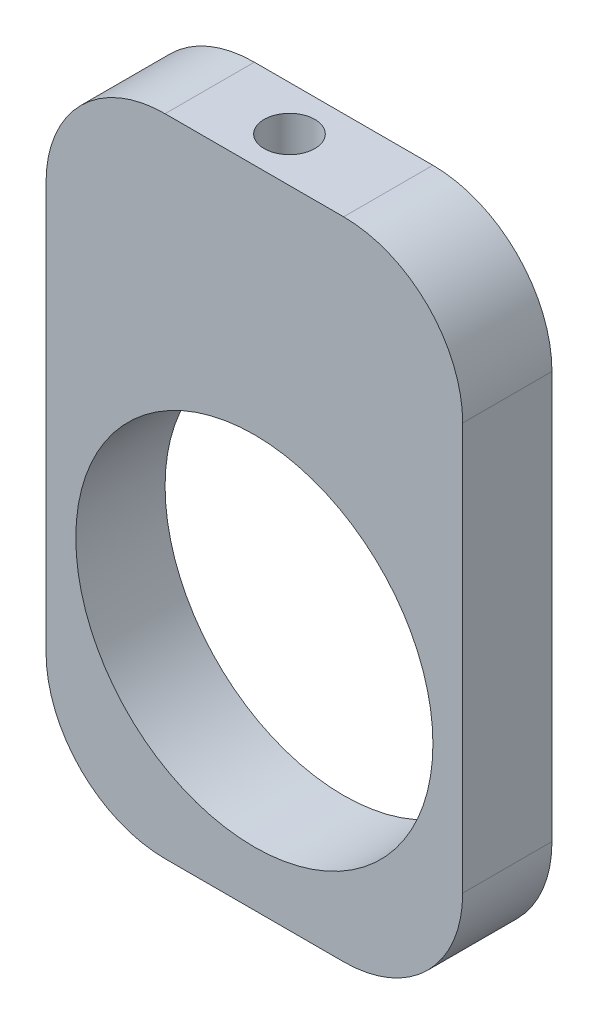
SolidWorks part; units mm, degrees
material "6063-O"
ref_plane "Front" through (0, 0, 0) normal (0, 0, 1) x (1, 0, 0)
ref_plane "Top" through (0, 0, 0) normal (0, 1, 0) x (1, 0, 0)
ref_plane "Right" through (0, 0, 0) normal (1, 0, 0) x (0, 0, -1)
sketch "Sketch1" plane through (0, 0, 0) normal (0, 0, 1) x (1, 0, 0)
  line L0 (11.1125, 12.446) -> (11.1125, 15.621)
  line L1 (4.7625, -12.446) -> (-4.7625, -12.446)
  line L2 (11.1125, -6.096) -> (11.1125, 12.446)
  line L3 (11.1125, 12.446) -> (-11.1125, 12.446)
  line L4 (-11.1125, -6.096) -> (-11.1125, 12.446)
  line L5 (11.1125, -12.446) -> (-11.1125, 12.446) construction
  line L6 (11.1125, 12.446) -> (-11.1125, -12.446) construction
  line L7 (4.7625, 21.971) -> (-4.7625, 21.971)
  line L8 (-11.1125, 15.621) -> (-11.1125, 12.446)
  circle A0 centre (0, 0) radius 9.525
  arc A1 (-11.1125, -6.096) -> (-4.7625, -12.446) centre (-4.7625, -6.096) ccw
  arc A2 (4.7625, -12.446) -> (11.1125, -6.096) centre (4.7625, -6.096) ccw
  arc A3 (11.1125, 15.621) -> (4.7625, 21.971) centre (4.7625, 15.621) ccw
  arc A4 (-4.7625, 21.971) -> (-11.1125, 15.621) centre (-4.7625, 15.621) ccw
  point P0 (0, 0)
  point P18 (11.1125, 21.971)
  dimension "D3" = 19.05
  dimension "D5" = 6.35
  dimension "D1" = 22.225
  dimension "D2" = 24.892
  dimension "D4" = 9.525
extrude "Boss-Extrude2" add sketch "Sketch1" along normal blind 4.7625 contours L7 A4 L8 L3 L0 A3 | L1 A2 L2 L3 L4 A1 A0
sketch "Sketch2" plane through (0, 21.971, 0) normal (0, 1, 0) x (1, 0, 0)
  line L0 (-11.1125, -2.3813) -> (-0.508, -2.3813)
  line L1 (-11.1125, -4.7625) -> (-11.1125, 0) construction
  line L2 (4.7625, -4.7625) -> (4.7625, 0) construction
  circle A0 centre (-0.508, -2.3813) radius 1.5875
  point P7 (4.7625, -2.3813)
  dimension "D2" = 3.175
  dimension "D1" = 10.6045
hole_wizard "Tap Drill for #6-32 Tap1" positions "Sketch5" profile "Sketch4" hole size "#6-32" standard "ANSI Inch"
sketch "Sketch5" plane through (0, 21.971, 0) normal (0, 1, 0) x (1, 0, 0)
  point P0 (-0.508, -2.3813)
sketch "Sketch4" plane through (-0.508, 21.971, 2.3813) normal (1, 0, 0) x (0, 0, 1)
  line L0 (0, 0) -> (0, 19.8627)
  line L1 (0, 19.8627) -> (1.3525, 19.05)
  line L2 (1.3525, 19.05) -> (1.3525, 0)
  line L5 (1.3525, 0) -> (0, 0)
  line L10 (0, 19.8627) -> (-1.3526, 19.05) construction
  line L11 (0, -6.35) -> (0, 107.95) construction
  dimension "Hole Dia." = 2.7051
  dimension "Hole Depth" = 19.05
  dimension "Drill Angle" = 118
